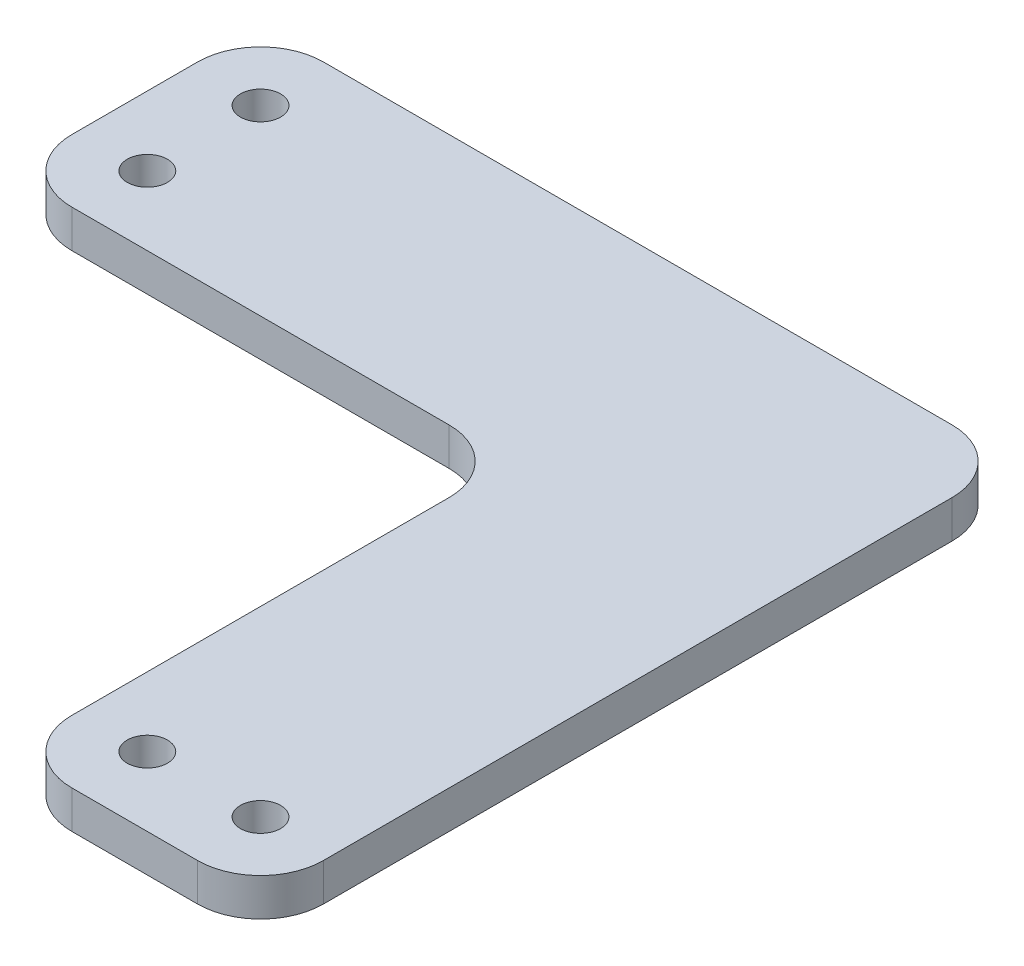
SolidWorks part; units mm, degrees
material "6061-T6 (SS)"
ref_plane "前视基准面" through (0, 0, 0) normal (0, 0, 1) x (1, 0, 0)
ref_plane "上视基准面" through (0, 0, 0) normal (0, 1, 0) x (1, 0, 0)
ref_plane "右视基准面" through (0, 0, 0) normal (1, 0, 0) x (0, 0, -1)
sketch "草图1" plane through (0, 0, 0) normal (0, 1, 0) x (1, 0, 0)
  line L0 (-50, 40) -> (-50, 20)
  line L1 (-10, 20) -> (10, 20) construction
  line L2 (-10, 20) -> (-10, -20) construction
  line L3 (-10, -20) -> (10, -20) construction
  line L4 (10, 20) -> (10, -20) construction
  line L5 (0, -20) -> (0, 20) construction
  line L6 (-10, 0) -> (10, 0) construction
  line L7 (10, 20) -> (-50, 20) construction
  line L8 (10, 20) -> (10, 40) construction
  line L9 (10, 40) -> (-50, 40) construction
  line L10 (-50, 20) -> (-50, 40) construction
  line L11 (10, 20) -> (-50, 40) construction
  line L12 (10, 40) -> (-50, 20) construction
  line L13 (-50, 20) -> (-10, 20)
  line L14 (-10, 20) -> (-10, -20)
  line L15 (-10, -20) -> (10, -20)
  line L16 (10, -20) -> (10, 40)
  line L17 (10, 40) -> (-50, 40)
  point P0 (0, 0)
  point P7 (-20, 30)
  dimension "D1" = 20
  dimension "D2" = 40
  dimension "D3" = 20
  dimension "D4" = 60
extrude "凸台-拉伸1" add sketch "草图1" along normal blind 3
sketch "草图2" plane through (0, 3, 0) normal (0, 1, 0) x (1, 0, 0)
  line L0 (10, -20) -> (10, 40) construction
  line L1 (-10, -20) -> (10, -20) construction
  line L2 (-10, -20) -> (-10, 0) construction
  line L3 (-10, 0) -> (10, 0) construction
  line L4 (10, -20) -> (10, 0) construction
  line L5 (-10, -20) -> (10, 0) construction
  line L6 (-10, 0) -> (10, -20) construction
  line L7 (10, 40) -> (-50, 40) construction
  line L8 (-50, 20) -> (-30, 20) construction
  line L9 (-50, 20) -> (-50, 40) construction
  line L10 (-50, 40) -> (-30, 40) construction
  line L11 (-30, 20) -> (-30, 40) construction
  line L12 (-50, 20) -> (-30, 40) construction
  line L13 (-50, 40) -> (-30, 20) construction
  line L15 (-44.5, 34.5) -> (-35.5, 34.5) construction
  line L16 (-44.5, 34.5) -> (-44.5, 25.5) construction
  line L17 (-44.5, 25.5) -> (-35.5, 25.5) construction
  line L18 (-35.5, 34.5) -> (-35.5, 25.5) construction
  line L19 (-40, 25.5) -> (-40, 34.5) construction
  line L20 (-44.5, 30) -> (-35.5, 30) construction
  line L21 (-4.5, -5.5) -> (4.5, -5.5) construction
  line L22 (-4.5, -5.5) -> (-4.5, -14.5) construction
  line L23 (-4.5, -14.5) -> (4.5, -14.5) construction
  line L24 (4.5, -5.5) -> (4.5, -14.5) construction
  line L25 (0, -14.5) -> (0, -5.5) construction
  line L26 (-4.5, -10) -> (4.5, -10) construction
  circle A0 centre (-44.5, 34.5) radius 1.6
  circle A1 centre (-44.5, 25.5) radius 1.6
  circle A2 centre (-4.5, -14.5) radius 1.6
  circle A3 centre (4.5, -14.5) radius 1.6
  point P4 (0, -10)
  point P12 (-40, 30)
  point P16 (-40, 30)
  point P20 (0, -10)
  dimension "D1" = 20
  dimension "D2" = 20
  dimension "D3" = 9
  dimension "D4" = 9
  dimension "D5" = 9
  dimension "D6" = 9
extrude "切除-拉伸1" cut sketch "草图2" against normal through all
fillet "圆角1" radius 5 6 edges at (10, 1.5, -40) (-50, 1.5, -40) (10, 1.5, 20) (-10, 1.5, 20) (-10, 1.5, -20) (-50, 1.5, -20)
